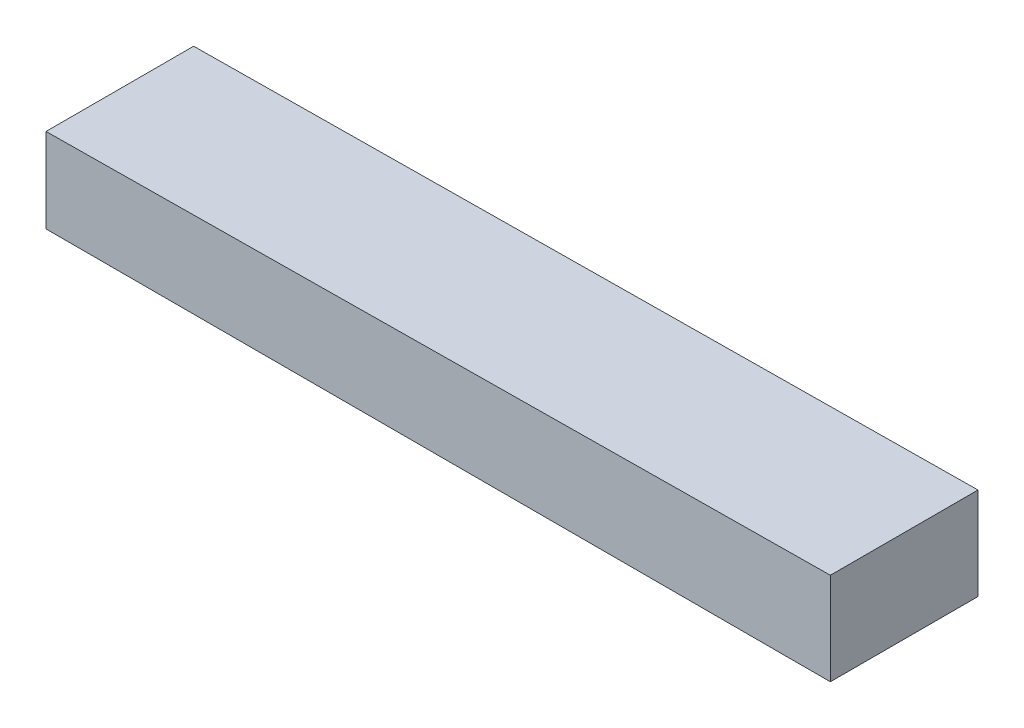
SolidWorks part; units mm, degrees
material "Gray Cast Iron"
ref_plane "Front Plane" through (0, 0, 0) normal (0, 0, 1) x (1, 0, 0)
ref_plane "Top Plane" through (0, 0, 0) normal (0, 1, 0) x (1, 0, 0)
ref_plane "Right Plane" through (0, 0, 0) normal (1, 0, 0) x (0, 0, -1)
sketch "Sketch1" plane through (0, 0, 0) normal (0, 0, 1) x (1, 0, 0)
  line L0 (0, 0) -> (-85, 0)
  line L1 (-85, 0) -> (-85, 9.15)
  line L2 (-85, 9.15) -> (0, 10)
  line L3 (0, 10) -> (0, 0)
  dimension "D1" = 85
  dimension "D2" = 10
  dimension "D3" = 9.15
extrude "Boss-Extrude1" add sketch "Sketch1" along normal blind 16
